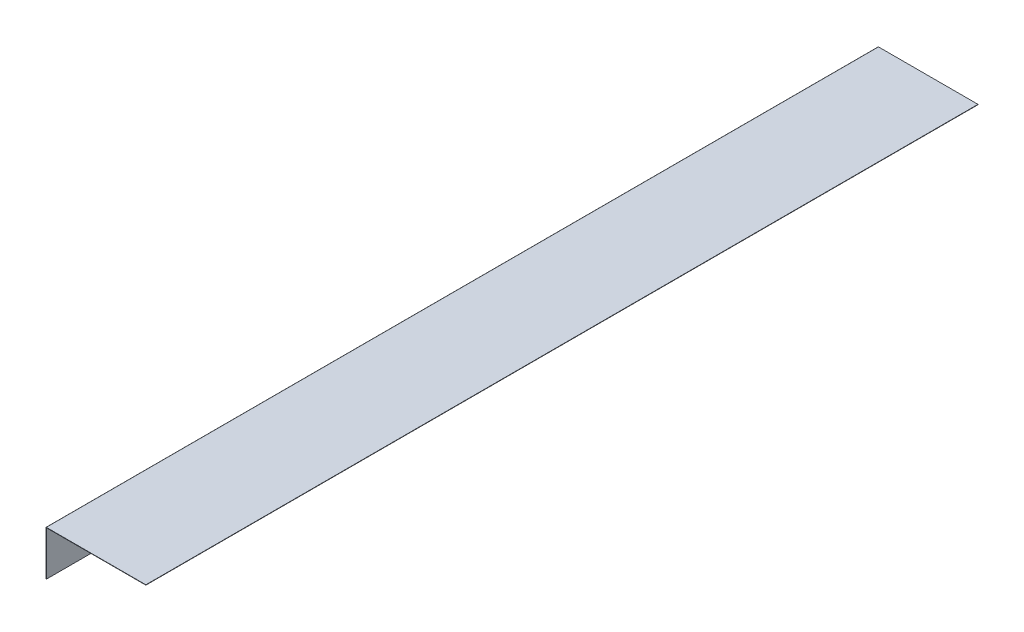
SolidWorks part; units mm, degrees
ref_plane "Front Plane" through (0, 0, 0) normal (0, 0, 1) x (1, 0, 0)
ref_plane "Top Plane" through (0, 0, 0) normal (0, 1, 0) x (1, 0, 0)
ref_plane "Right Plane" through (0, 0, 0) normal (1, 0, 0) x (0, 0, -1)
sketch "Sketch1" plane through (0, 0, 0) normal (0, 0, 1) x (1, 0, 0)
  line L0 (0, 0) -> (0, 135)
  line L1 (0, 135) -> (300, 135)
  line L2 (300, 135) -> (300, 134)
  line L3 (300, 134) -> (1, 134)
  line L4 (1, 134) -> (1, 0)
  line L5 (1, 0) -> (0, 0)
  dimension "D1" = 1
  dimension "D2" = 1
  dimension "D3" = 300
  dimension "D4" = 135
extrude "Boss-Extrude1" add sketch "Sketch1" along normal blind 2500
fillet "Fillet1" radius 1 2 edges at (0, 135, 1250) (1, 134, 1250)
